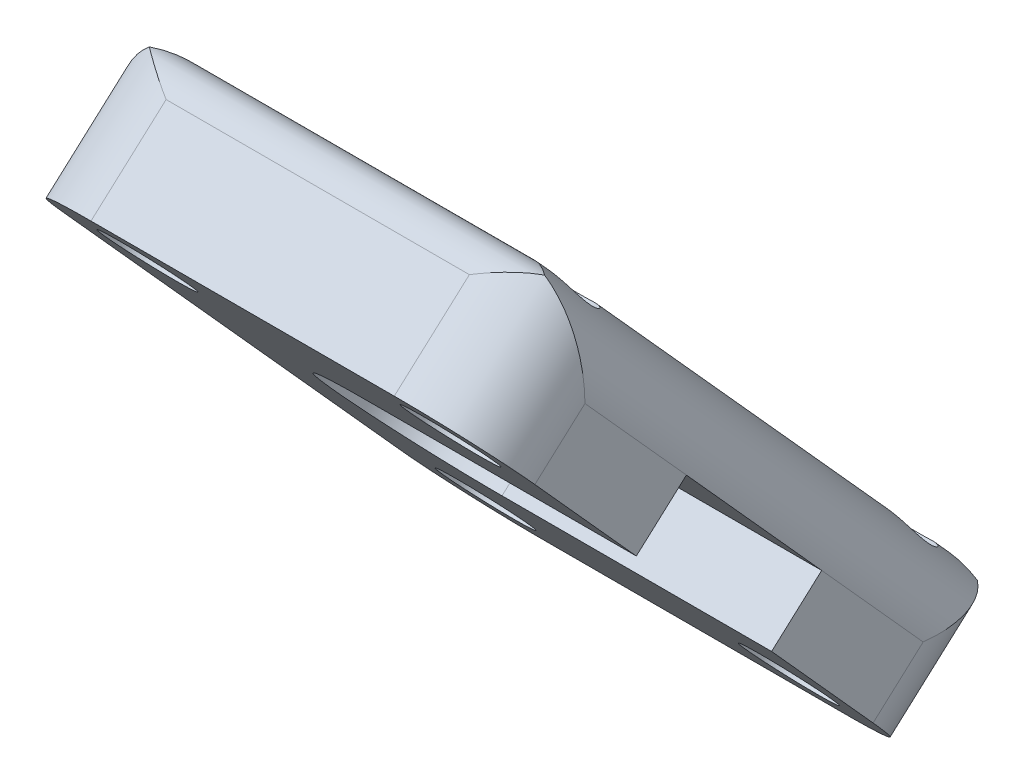
SolidWorks part; units mm, degrees
ref_plane "前视基准面" through (0, 0, 0) normal (0, 0, 1) x (1, 0, 0)
ref_plane "上视基准面" through (0, 0, 0) normal (0, 1, 0) x (1, 0, 0)
ref_plane "右视基准面" through (0, 0, 0) normal (1, 0, 0) x (0, 0, -1)
other "Configuration Table"
sketch "草图2" plane through (0, 0, 0) normal (0, 0, 1) x (1, 0, 0)
  line L0 (14, 0) -> (-14, 0)
  line L1 (-14, 0) -> (-14, 4)
  line L2 (-10, 8) -> (10, 8)
  line L4 (14, 0) -> (14, 4)
  arc A0 (-14, 4) -> (-10, 8) centre (-10, 4) cw
  arc A1 (14, 4) -> (10, 8) centre (10, 4) ccw
  point P12 (0, 8)
  point P13 (0, 0)
  dimension "D3" = 4
  dimension "D4" = 4
  dimension "D1" = 14
  dimension "D2" = 8
  dimension "D5" = 4
extrude "凸台-拉伸1" add sketch "草图2" against normal blind 40
sketch "草图3" plane through (0, 0, 0) normal (0, 1, 0) x (1, 0, 0)
  line L0 (-10, 20) -> (-25.1467, 20) construction
  line L1 (-10, 40) -> (-10, 0) construction
  circle A0 centre (-9, 35) radius 2.5
  circle A1 centre (9, 35) radius 2.5
  circle A2 centre (-9, 5) radius 2.5
  circle A3 centre (9, 5) radius 2.5
  dimension "D1" = 5
  dimension "D4" = 9
  dimension "D2" = 15
  dimension "D3" = 15
  dimension "D5" = 9
extrude "切除-拉伸1" cut sketch "草图3" along normal through all
sketch "草图5" plane through (0, 8, 0) normal (0, 1, 0) x (1, 0, 0)
  line L1 (14, 0) -> (14, 40) construction
  line L4 (-14, 40) -> (-14, 0) construction
  line L6 (10, 40) -> (-10, 40) construction
  line L7 (-10, 0) -> (10, 0) construction
  line L9 (14, 5) -> (14, 35)
  line L12 (-14, 35) -> (-14, 5)
  line L14 (9, 40) -> (-9, 40)
  line L15 (-9, 0) -> (9, 0)
  arc A16 (9, 40) -> (14, 35) centre (9, 35) cw
  arc A17 (14, 5) -> (9, 0) centre (9, 5) cw
  arc A18 (-9, 0) -> (-14, 5) centre (-9, 5) cw
  arc A19 (-14, 35) -> (-9, 40) centre (-9, 35) cw
  dimension "D1" = 5
extrude "切除-拉伸3" cut sketch "草图5" against normal through all flip side to cut
sketch "草图6" plane through (0, 0, 0) normal (0, -1, 0) x (1, 0, 0)
  line L0 (14, -20) -> (-2, -20) construction
  line L1 (14, -35) -> (14, -5) construction
  line L2 (14, -26) -> (-2, -26)
  line L3 (14, -14) -> (-2, -14)
  arc A0 (14, -26) -> (14, -14) centre (14, -20) ccw
  arc A1 (-2, -14) -> (-2, -26) centre (-2, -20) ccw
  point P4 (6, -20)
  dimension "D1" = 6
  dimension "D2" = 16
extrude "切除-拉伸4" cut sketch "草图6" against normal blind 4
move or copy body "实体-移动/复制1" bodies to move or copy 109 copy no rotation origin (0, 4, -20) rotation axis (-1, 0, 0) rotation angle 48
sketch "草图7" plane through (-14, 0, 0) normal (-1, 0, 0) x (0, 0, 1)
  line L0 (-6.9905, 12.4706) -> (-3.6448, 16.1864) construction
  line L1 (-3.6448, 16.1864) -> (-9.59, 21.5394) construction
  line L4 (-36.3552, -8.1864) -> (-30.41, -13.5394) construction
  line L5 (-30.41, -13.5394) -> (-27.0644, -9.8237) construction
  line L6 (-9.6576, 21.4643) -> (-11.4024, 19.5265) construction
  line L7 (-14.4688, 16.1209) -> (-31.4764, -2.7679) construction
  line L8 (-34.5427, -6.1734) -> (-36.2876, -8.1113) construction
  line L9 (-27.0644, -9.8237) -> (-6.9905, 12.4706) construction
  line L10 (-6.9905, 12.4706) -> (-3.6448, 16.1864)
  line L11 (-3.6448, 16.1864) -> (-8.1037, 20.2012)
  line L14 (-34.8689, -9.5246) -> (-30.41, -13.5394)
  line L15 (-30.41, -13.5394) -> (-27.0644, -9.8237)
  line L16 (-10.9282, 20.0531) -> (-11.4024, 19.5265)
  line L17 (-14.4688, 16.1209) -> (-31.4764, -2.7679)
  line L18 (-34.5427, -6.1734) -> (-35.0169, -6.7001)
  line L19 (-27.0644, -9.8237) -> (-6.9905, 12.4706)
  line L20 (-31.4764, -2.7679) -> (-34.5427, -6.1734)
  line L21 (-14.4688, 16.1209) -> (-11.4024, 19.5265)
  arc A0 (-35.0169, -6.7001) -> (-34.8689, -9.5246) centre (-33.5306, -8.0383) ccw
  arc A1 (-8.1037, 20.2012) -> (-10.9282, 20.0531) centre (-9.4419, 18.7149) ccw
  dimension "D1" = 4
  dimension "D2" = 4
extrude "切除-拉伸6" cut sketch "草图7" against normal blind 50 flip side to cut
ref_plane "基准面1" through (0, 10, 0) normal (0, 1, 0) x (1, 0, 0)
sketch "草图9" plane through (0, 10, 0) normal (0, 1, 0) x (1, 0, 0)
  line L1 (-15.6639, 18.0182) -> (15.6639, 18.0182)
  line L2 (-15.6639, 18.0182) -> (-15.6639, 21.95)
  line L3 (-15.6639, 21.95) -> (15.6639, 21.95)
  line L4 (15.6639, 18.0182) -> (15.6639, 21.95)
  line L5 (-15.6639, 18.0182) -> (15.6639, 21.95) construction
  line L6 (-15.6639, 21.95) -> (15.6639, 18.0182) construction
  point P0 (0, 19.9841)
